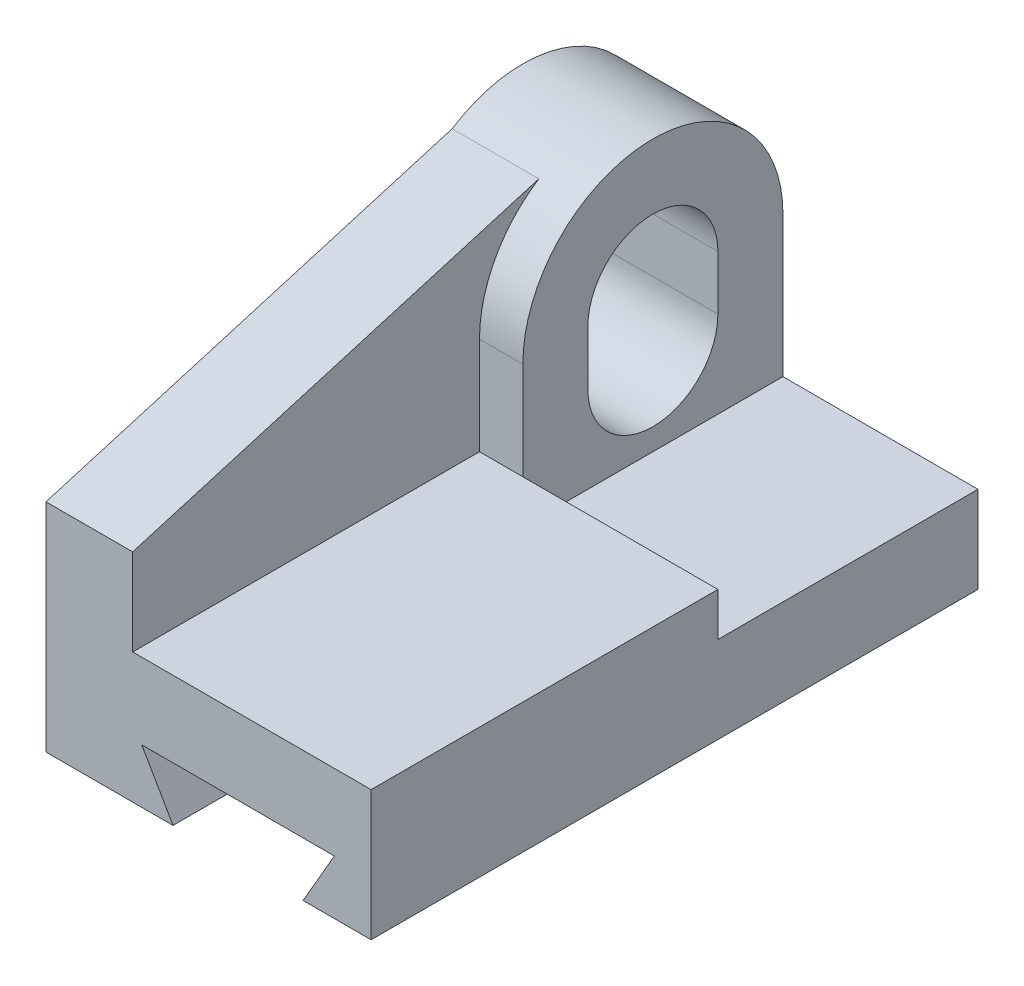
SolidWorks part; units mm, degrees
ref_plane "前视基准面" through (0, 0, 0) normal (0, 0, 1) x (1, 0, 0)
ref_plane "上视基准面" through (0, 0, 0) normal (0, 1, 0) x (1, 0, 0)
ref_plane "右视基准面" through (0, 0, 0) normal (1, 0, 0) x (0, 0, -1)
other "Configuration Table"
sketch "草图1" plane through (0, 0, 0) normal (1, 0, 0) x (0, 0, -1)
  line L0 (0, 12) -> (32, 12)
  line L1 (0, 0) -> (56, 0)
  line L2 (0, 0) -> (0, 20)
  line L3 (0, 20) -> (56, 20)
  line L4 (56, 0) -> (56, 20)
  line L5 (32, 12) -> (32, 0)
  line L6 (32, 0) -> (32, 8)
  line L7 (32, 8) -> (56, 8)
  line L8 (56, 8) -> (56, 21)
  line L9 (32, 12) -> (32, 21)
  line L10 (32, 21) -> (56, 21)
  line L11 (44, 21) -> (44, 16) construction
  line L12 (50, 21) -> (50, 16)
  line L13 (38, 21) -> (38, 16)
  line L14 (0, 20) -> (44, 33)
  arc A0 (32, 21) -> (56, 21) centre (44, 21) cw
  arc A1 (50, 21) -> (38, 21) centre (44, 21) ccw
  arc A2 (38, 16) -> (50, 16) centre (44, 16) ccw
  point P14 (44, 18.5)
  dimension "D6" = 5
  dimension "D8" = 6
  dimension "D1" = 56
  dimension "D2" = 20
  dimension "D3" = 8
  dimension "D4" = 12
  dimension "D5" = 32
  dimension "D7" = 8
extrude "凸台-拉伸4" add sketch "草图1" along normal blind 30 contours L5 L0 L2 L1 | L7 L5 L1 L4
sketch "草图2" plane through (0, 0, 0) normal (-1, 0, 0) x (0, 0, 1)
  line L0 (-32, 8) -> (-32, 21)
  line L1 (-32, 21) -> (-56, 21)
  line L2 (-56, 21) -> (-56, 8)
  line L3 (-32, 8) -> (-56, 8) construction
  line L4 (-44, 21) -> (-44, 16) construction
  line L5 (-38, 21) -> (-38, 16)
  line L6 (-50, 21) -> (-50, 16)
  arc A0 (-56, 21) -> (-32, 21) centre (-44, 21) cw
  arc A1 (-38, 21) -> (-50, 21) centre (-44, 21) ccw
  arc A2 (-50, 16) -> (-38, 16) centre (-44, 16) ccw
  point P10 (-44, 18.5)
  line M2 (-32, 12) -> (-32, 8)
  line M3 (-32, 8) -> (-56, 8)
  dimension "D1" = 13
extrude "凸台-拉伸5" add sketch "草图2" against normal blind 12 contours A1 L1 A0 | A2 L6 L1 L2 L0 L5 M3 M2
sketch "草图3" plane through (0, 0, 0) normal (-1, 0, 0) x (0, 0, 1)
  line L0 (-44, 33) -> (0, 20)
  line L1 (0, 20) -> (0, 12)
  line L2 (0, 12) -> (-32, 12) construction
  line L8 (0, 12) -> (-32, 12)
  line L9 (-32, 12) -> (-32, 21)
  line L10 (-56, 21) -> (-56, 0)
  line L11 (-56, 0) -> (0, 0)
  line L12 (0, 0) -> (0, 12)
  line L13 (0, 12) -> (-32, 12)
  line L14 (-32, 12) -> (-32, 21)
  arc A0 (-32, 21) -> (-56, 21) centre (-44, 21) ccw construction
  arc A2 (-32, 21) -> (-56, 21) centre (-44, 21) ccw
  arc A3 (-32, 21) -> (-44, 33) centre (-44, 21) ccw
  line M7 (0, 12) -> (-32, 12)
  line M8 (-32, 12) -> (-32, 21)
  arc M9 (-32, 21) -> (-56, 21) centre (-44, 21) ccw
  dimension "D1" = 0
extrude "凸台-拉伸6" add sketch "草图3" against normal blind 8 contours L1 L0 M9 M8 M7
sketch "草图4" plane through (0, 0, 0) normal (0, 0, 1) x (1, 0, 0)
  line L0 (30, 0) -> (0, 0) construction
  line L1 (17.7208, 0) -> (17.7208, 26.514) construction
  line L2 (17.7208, 0) -> (11.7208, 0)
  line L3 (11.7208, 0) -> (8.834, 5)
  line L4 (8.834, 5) -> (26.6075, 5)
  line L5 (17.7208, 0) -> (23.7208, 0)
  line L6 (23.7208, 0) -> (26.6075, 5)
  point P2 (14.7208, 0)
  point P10 (17.7208, 5)
  dimension "D1" = 5
  dimension "D2" = 6
  dimension "D3" = 120
extrude "切除-拉伸1" cut sketch "草图4" against normal through all
